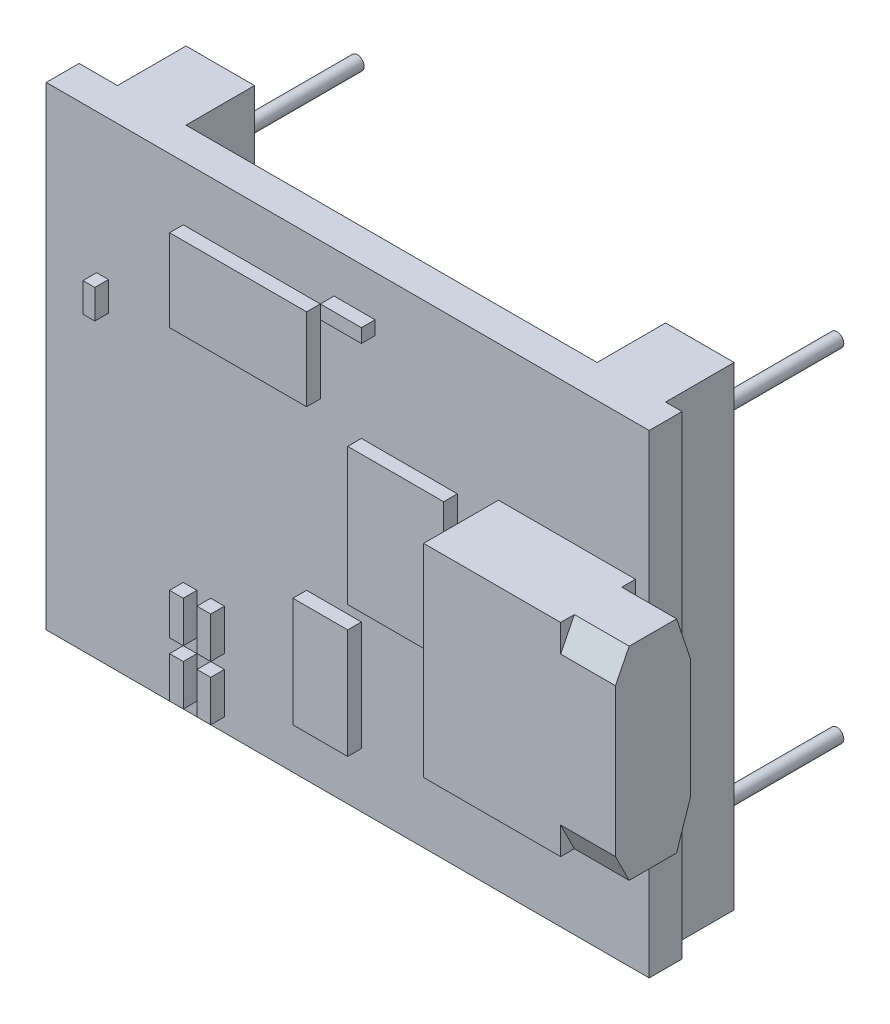
SolidWorks part; units mm, degrees
ref_plane "Plan de face" through (0, 0, 0) normal (0, 0, 1) x (1, 0, 0)
ref_plane "Plan de dessus" through (0, 0, 0) normal (0, 1, 0) x (1, 0, 0)
ref_plane "Plan de droite" through (0, 0, 0) normal (1, 0, 0) x (0, 0, -1)
sketch "Esquisse1" plane through (0, 0, 0) normal (0, 0, 1) x (1, 0, 0)
  line L1 (0, 0) -> (-22, 0)
  line L2 (0, 0) -> (0, 17.3)
  line L3 (0, 17.3) -> (-22, 17.3)
  line L4 (-22, 0) -> (-22, 17.3)
  dimension "D1" = 22
  dimension "D2" = 17.3
extrude "Boss.-Extru.1" add sketch "Esquisse1" along normal blind 1.2
sketch "Esquisse2" plane through (0, 0, 1.2) normal (0, 0, 1) x (1, 0, 0)
  line L0 (0, 0) -> (0, 17.3) construction
  line L1 (5.5, 4.95) -> (-5.5, 4.95)
  line L2 (5.5, 4.95) -> (5.5, 12.35)
  line L3 (5.5, 12.35) -> (-5.5, 12.35)
  line L4 (-5.5, 4.95) -> (-5.5, 12.35)
  line L5 (5.5, 4.95) -> (-5.5, 12.35) construction
  line L6 (5.5, 12.35) -> (-5.5, 4.95) construction
  line L7 (0, 12.35) -> (1.5, 12.35) construction
  line L8 (1.5, 12.35) -> (1.5, 4.95)
  point P0 (0, 8.65)
  line M5 (0, 0) -> (0, 17.3)
  dimension "D1" = 7.4
  dimension "D2" = 11
  dimension "D3" = 1.5
extrude "Boss.-Extru.2" add sketch "Esquisse2" along normal blind 2.73 contours L4 L1 L3 M5 | L8 L3 L1 M5
sketch "Esquisse5" plane through (0, 0, 1.2) normal (0, 0, 1) x (1, 0, 0)
  line L0 (-22, 0) -> (0, 0) construction
  line L1 (-10.5, 2) -> (-12.5, 2)
  line L2 (-10.5, 2) -> (-10.5, 6)
  line L3 (-10.5, 6) -> (-12.5, 6)
  line L4 (-12.5, 2) -> (-12.5, 6)
  line L5 (-15.5, 0.5) -> (-16, 0.5)
  line L6 (-15.5, 0.5) -> (-15.5, 2)
  line L7 (-15.5, 2) -> (-16, 2)
  line L8 (-16, 0.5) -> (-16, 2)
  line L9 (-16.5, 0.5) -> (-17, 0.5)
  line L10 (-16.5, 0.5) -> (-16.5, 2)
  line L11 (-16.5, 2) -> (-17, 2)
  line L12 (-17, 0.5) -> (-17, 2)
  line L13 (-15.5, 2.5) -> (-16, 2.5)
  line L14 (-15.5, 2.5) -> (-15.5, 4)
  line L15 (-15.5, 4) -> (-16, 4)
  line L16 (-16, 2.5) -> (-16, 4)
  line L17 (-16.5, 2.5) -> (-17, 2.5)
  line L18 (-16.5, 2.5) -> (-16.5, 4)
  line L19 (-16.5, 4) -> (-17, 4)
  line L20 (-17, 2.5) -> (-17, 4)
  line L21 (-12, 12.3) -> (-17, 12.3)
  line L22 (-12, 12.3) -> (-12, 15.3)
  line L23 (-12, 15.3) -> (-17, 15.3)
  line L24 (-17, 12.3) -> (-17, 15.3)
  line L25 (-10, 15.3) -> (-11.5, 15.3)
  line L26 (-10, 15.3) -> (-10, 15.8)
  line L27 (-10, 15.8) -> (-11.5, 15.8)
  line L28 (-11.5, 15.3) -> (-11.5, 15.8)
  line L33 (-19.7273, 11.1459) -> (-20.1614, 11.1459)
  line L34 (-19.7273, 11.1459) -> (-19.7273, 12.207)
  line L35 (-19.7273, 12.207) -> (-20.1614, 12.207)
  line L36 (-20.1614, 11.1459) -> (-20.1614, 12.207)
  line L37 (-22, 17.3) -> (-22, 0) construction
  line L38 (0, 17.3) -> (-22, 17.3) construction
  line L39 (-5.5, 4.95) -> (-5.5, 12.35) construction
  line L40 (-7, 6.8) -> (-10.5, 6.8)
  line L41 (-7, 6.8) -> (-7, 11.8)
  line L42 (-7, 11.8) -> (-10.5, 11.8)
  line L43 (-10.5, 6.8) -> (-10.5, 11.8)
  point P36 (-15.75, 2.5)
  point P37 (-16.75, 2.5)
  dimension "D1" = 2
  dimension "D2" = 4
  dimension "D3" = 1.5
  dimension "D4" = 1.5
  dimension "D5" = 1.5
  dimension "D6" = 1.5
  dimension "D7" = 0.5
  dimension "D8" = 0.5
  dimension "D9" = 0.5
  dimension "D10" = 0.5
  dimension "D11" = 0.5
  dimension "D12" = 0.5
  dimension "D13" = 0.5
  dimension "D14" = 0.5
  dimension "D15" = 0
  dimension "D16" = 0.5
  dimension "D17" = 5
  dimension "D18" = 3
  dimension "D19" = 2
  dimension "D20" = 5
  dimension "D21" = 3
  dimension "D22" = 2
  dimension "D23" = 5
  dimension "D26" = 1.5
  dimension "D27" = 0.5
  dimension "D28" = 1.5
  dimension "D29" = 12
  dimension "D31" = 3.5
  dimension "D32" = 5
  dimension "D33" = 1.5
  dimension "D34" = 5.5
extrude "Boss.-Extru.5" add sketch "Esquisse5" along normal blind 0.5
sketch "Esquisse8" plane through (1.5, 0, 0) normal (1, 0, 0) x (0, 0, -1)
  line L0 (-1.2, 4.95) -> (-1.2, 6.45) construction
  line L1 (-1.2, 4.95) -> (-1.2, 12.35) construction
  line L2 (-1.2, 6.45) -> (-1.2, 10.85) construction
  line L3 (-1.2, 12.35) -> (-1.2, 4.95) construction
  line L4 (-1.2, 10.85) -> (-1.2, 12.35) construction
  line L5 (-1.2, 6.45) -> (-1.2, 4.95)
  line L6 (-1.2, 4.95) -> (-1.7, 4.95)
  line L7 (-1.7, 2) -> (-1.7, 6) construction
  line L8 (-3.93, 4.95) -> (-1.2, 4.95) construction
  line L9 (-1.7, 4.95) -> (-1.2, 6.45)
  line L10 (-1.2, 10.85) -> (-1.7, 12.35)
  line L11 (-3.93, 12.35) -> (-1.2, 12.35) construction
  line L12 (-1.7, 12.3) -> (-1.7, 15.3) construction
  line L13 (-1.7, 12.35) -> (-1.2, 12.35)
  line L14 (-1.2, 12.35) -> (-1.2, 10.85)
  line L15 (-3.93, 4.95) -> (-3.93, 5.95) construction
  line L16 (-3.93, 12.35) -> (-3.93, 4.95) construction
  line L17 (-3.93, 5.95) -> (-3.93, 11.35) construction
  line L18 (-3.93, 11.35) -> (-3.93, 12.35) construction
  line L19 (-3.93, 12.35) -> (-3.43, 12.35) construction
  line L20 (-3.43, 12.35) -> (-3.43, 4.95) construction
  line L21 (-3.43, 4.95) -> (-3.93, 4.95) construction
  line L22 (-3.93, 4.95) -> (-3.93, 5.95)
  line L23 (-3.93, 5.95) -> (-3.43, 4.95)
  line L24 (-3.43, 4.95) -> (-3.93, 4.95)
  line L25 (-3.93, 11.35) -> (-3.43, 12.35)
  line L26 (-3.43, 12.35) -> (-3.93, 12.35)
  line L27 (-3.93, 12.35) -> (-3.93, 11.35)
  dimension "D1" = 1.5
  dimension "D2" = 1.5
  dimension "D3" = 1
  dimension "D4" = 0.5
  dimension "D5" = 1
extrude "Enlèv. mat.-Extru.4" cut sketch "Esquisse8" against normal blind 2
sketch "Esquisse11" plane through (0, 0, 0) normal (0, 0, -1) x (-1, 0, 0)
  line L0 (22, 0) -> (0, 0) construction
  line L1 (0.6, 0) -> (3.1, 0)
  line L2 (0.6, 0) -> (0.6, 17.3)
  line L3 (0.6, 17.3) -> (3.1, 17.3)
  line L4 (3.1, 0) -> (3.1, 17.3)
  line L5 (0, 17.3) -> (22, 17.3) construction
  line L6 (22, 17.3) -> (22, 0) construction
  line L7 (18.1, 0) -> (20.6, 0)
  line L8 (18.1, 0) -> (18.1, 17.3)
  line L9 (18.1, 17.3) -> (20.6, 17.3)
  line L10 (20.6, 0) -> (20.6, 17.3)
  line L11 (0, 0) -> (0, 17.3) construction
  dimension "D1" = 2.5
  dimension "D2" = 2.5
  dimension "D3" = 1.4
  dimension "D4" = 0.6
extrude "Boss.-Extru.8" add sketch "Esquisse11" along normal blind 2.5
sketch "Esquisse12" plane through (0, 0, -2.5) normal (0, 0, -1) x (-1, 0, 0)
  line L0 (1.85, 0) -> (1.85, 17.3) construction
  line L1 (0.6, 0) -> (3.1, 0) construction
  line L2 (3.1, 17.3) -> (0.6, 17.3) construction
  line L3 (19.35, 0) -> (19.35, 17.3) construction
  line L4 (18.1, 0) -> (20.6, 0) construction
  line L5 (20.6, 17.3) -> (18.1, 17.3) construction
  line L6 (1.85, 2.4) -> (1.85, 14.9)
  line L7 (19.35, 2.4) -> (19.35, 14.9)
  circle A0 centre (1.85, 2.4) radius 0.25
  circle A1 centre (1.85, 14.9) radius 0.25
  circle A2 centre (19.35, 14.9) radius 0.25
  circle A3 centre (19.35, 2.4) radius 0.25
  point P15 (1.85, 8.65)
  point P18 (19.35, 8.65)
  dimension "D3" = 0.5
  dimension "D4" = 0.5
  dimension "D5" = 0.5
  dimension "D6" = 0.5
  dimension "D1" = 12.5
  dimension "D2" = 12.5
extrude "Boss.-Extru.9" add sketch "Esquisse12" along normal blind 5
